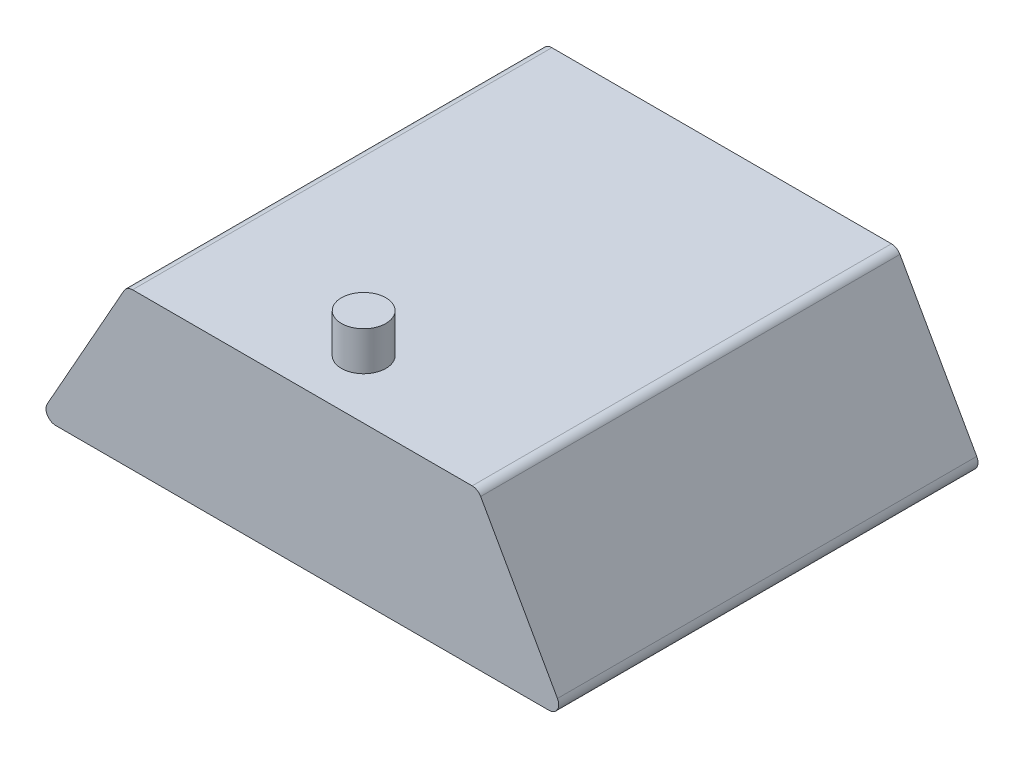
SolidWorks part; units mm, degrees
ref_plane "前基準面" through (0, 0, 0) normal (0, 0, 1) x (1, 0, 0)
ref_plane "上基準面" through (0, 0, 0) normal (0, 1, 0) x (1, 0, 0)
ref_plane "右基準面" through (0, 0, 0) normal (1, 0, 0) x (0, 0, -1)
sketch "草圖1" plane through (0, 0, 0) normal (0, 0, 1) x (1, 0, 0)
  line L0 (-130.8086, -66.7692) -> (-91.4336, 3.2308)
  line L1 (-126.4508, -74.2205) -> (126.4508, -74.2205)
  line L5 (-87.0758, 5.7795) -> (87.0758, 5.7795)
  line L6 (91.4336, 3.2308) -> (130.8086, -66.7692)
  line L7 (0, 5.7795) -> (0, -74.2205) construction
  arc A0 (-126.4508, -74.2205) -> (-130.8086, -66.7692) centre (-126.4508, -69.2205) cw
  arc A1 (126.4508, -74.2205) -> (130.8086, -66.7692) centre (126.4508, -69.2205) ccw
  arc A2 (91.4336, 3.2308) -> (87.0758, 5.7795) centre (87.0758, 0.7795) ccw
  arc A3 (-91.4336, 3.2308) -> (-87.0758, 5.7795) centre (-87.0758, 0.7795) cw
  point P0 (0, 0)
  point P10 (-135, -74.2205)
  point P13 (135, -74.2205)
  point P16 (90, 5.7795)
  point P19 (-90, 5.7795)
  dimension "D6" = 5
  dimension "D1" = 270
  dimension "D2" = 180
  dimension "D3" = 80
  dimension "D4" = 135
  dimension "D5" = 0
extrude "填料-伸長1" add sketch "草圖1" along normal blind 215 contours L5 A2 L6 A1 L1 A0 L0 A3
sketch "草圖2" plane through (0, -74.2205, 0) normal (0, -1, 0) x (1, 0, 0)
  line L0 (0, 215) -> (0, 143.3672) construction
  line L1 (-126.4508, 215) -> (126.4508, 215) construction
  line L2 (-135, 107.5) -> (-42.8148, 107.5) construction
  line L3 (-135, 215) -> (-135, 0) construction
  circle A0 centre (-100, 185.9897) radius 12.5
  circle A1 centre (-100, 29.0103) radius 12.5
  circle A2 centre (100, 29.0103) radius 12.5
  circle A3 centre (100, 185.9897) radius 12.5
  dimension "D2" = 25
  dimension "D1" = 100
extrude "填料-伸長2" add sketch "草圖2" along normal blind 10 draft 15
sketch "Sketch1" plane through (0, 5.7795, 0) normal (0, 1, 0) x (1, 0, 0)
  line L2 (91.4336, -215) -> (91.4336, 0) construction
  line L4 (-87.0758, 0) -> (87.0758, 0) construction
  circle A0 centre (1.4336, -185) radius 11.4044
  dimension "D1" = 90
  dimension "D2" = 185
extrude "Boss-Extrude1" add sketch "Sketch1" along normal blind 20
sketch "Sketch2" plane through (0, 25.7795, 0) normal (0, 1, 0) x (1, 0, 0)
  circle A0 centre (1.4336, -185) radius 11.4044
sketch "Sketch3" plane through (0, 5.7795, 0) normal (0, 1, 0) x (1, 0, 0)
  circle A0 centre (1.4336, -185) radius 11.4044
